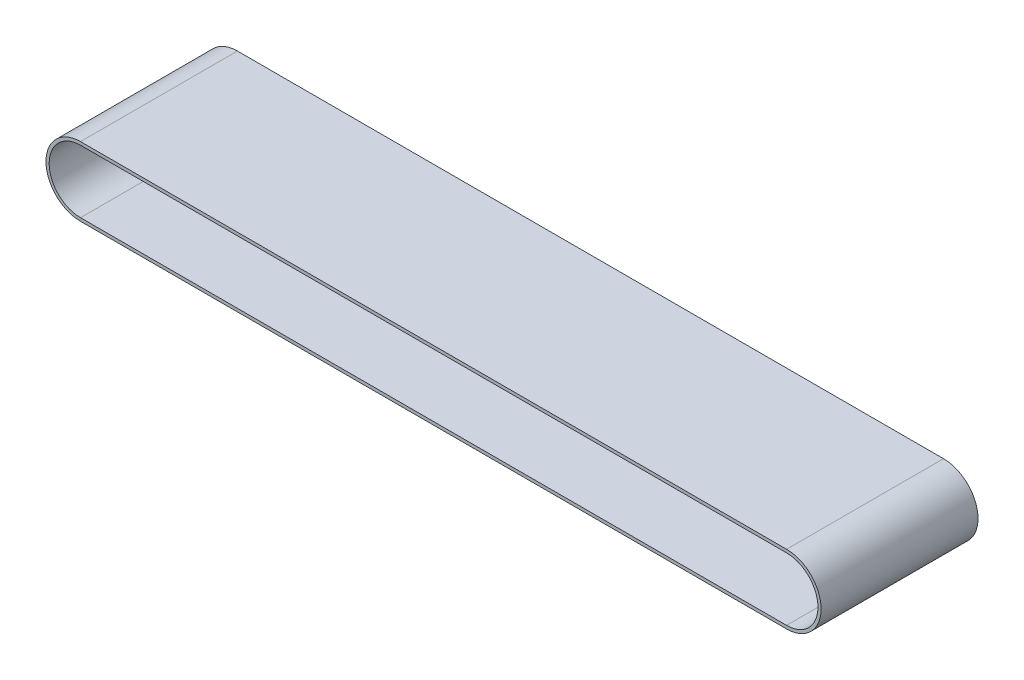
SolidWorks part; units mm, degrees
ref_plane "Front Plane" through (0, 0, 0) normal (0, 0, 1) x (1, 0, 0)
ref_plane "Top Plane" through (0, 0, 0) normal (0, 1, 0) x (1, 0, 0)
ref_plane "Right Plane" through (0, 0, 0) normal (1, 0, 0) x (0, 0, -1)
sketch "Sketch1" plane through (0, 0, 0) normal (0, 0, 1) x (1, 0, 0)
  line L0 (-371.3468, 20) -> (78.6532, 20)
  line L1 (78.6532, -24) -> (-371.3468, -24)
  arc A0 (-371.3468, 20) -> (-371.3468, -24) centre (-371.3468, -2) ccw
  arc A1 (78.6532, -24) -> (78.6532, 20) centre (78.6532, -2) ccw
  dimension "D1" = 44
  dimension "D2" = 44
  dimension "D3" = 450
extrude "Boss-Extrude1" add sketch "Sketch1" along normal blind 100
shell "Shell2" thickness 2
